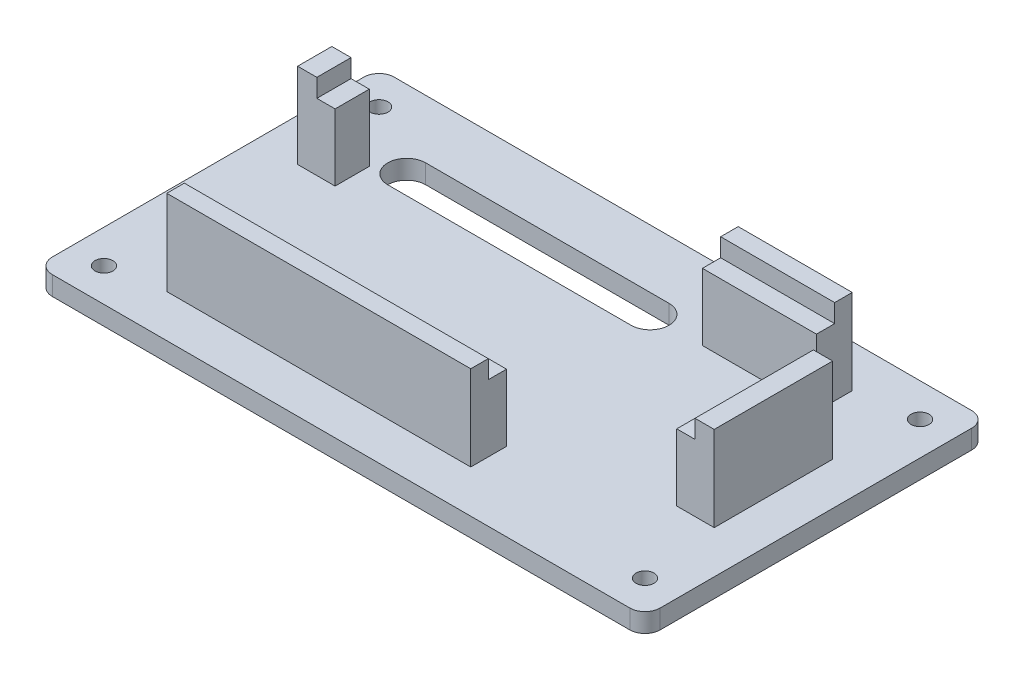
SolidWorks part; units mm, degrees
ref_plane "Front Plane" through (0, 0, 0) normal (0, 0, 1) x (1, 0, 0)
ref_plane "Top Plane" through (0, 0, 0) normal (0, 1, 0) x (1, 0, 0)
ref_plane "Right Plane" through (0, 0, 0) normal (1, 0, 0) x (0, 0, -1)
sketch "Sketch1" plane through (0, 0, 0) normal (0, 1, 0) x (1, 0, 0)
  line L1 (50.8, -28.575) -> (-50.8, -28.575)
  line L2 (50.8, -28.575) -> (50.8, 28.575)
  line L3 (50.8, 28.575) -> (-50.8, 28.575)
  line L4 (-50.8, -28.575) -> (-50.8, 28.575)
  line L5 (50.8, -28.575) -> (-50.8, 28.575) construction
  line L6 (50.8, 28.575) -> (-50.8, -28.575) construction
  point P0 (0, 0)
  dimension "D1" = 57.15
  dimension "D2" = 101.6
extrude "Boss-Extrude1" add sketch "Sketch1" along normal blind 3.175
sketch "Sketch10" plane through (0, 3.175, 0) normal (0, 1, 0) x (1, 0, 0)
  circle A0 centre (-45.212, -22.987) radius 1.5
  circle A1 centre (45.212, 22.987) radius 1.5
  circle A2 centre (-45.212, 22.987) radius 1.5
  circle A3 centre (45.212, -22.987) radius 1.5
  dimension "D1" = 3
extrude "Cut-Extrude3" cut sketch "Sketch10" against normal through all
fillet "Fillet1" radius 2.54 4 edges at (-50.8, 1.5875, 28.575) (-50.8, 1.5875, -28.575) (50.8, 1.5875, 28.575) (50.8, 1.5875, -28.575)
sketch "Sketch11" plane through (0, 3.175, 0) normal (0, 1, 0) x (1, 0, 0)
  line L0 (-33.2243, 15.6253) -> (7.4512, 15.6253) construction
  line L1 (-33.2243, 18.8003) -> (7.4512, 18.8003)
  line L2 (-33.2243, 12.4503) -> (7.4512, 12.4503)
  line L3 (48.26, 28.575) -> (-48.26, 28.575) construction
  arc A0 (-33.2243, 18.8003) -> (-33.2243, 12.4503) centre (-33.2243, 15.6253) ccw
  arc A1 (7.4512, 12.4503) -> (7.4512, 18.8003) centre (7.4512, 15.6253) ccw
  point P2 (-12.8866, 15.6253)
  dimension "D1" = 12.9497
  dimension "D2" = 3.175
extrude "Cut-Extrude4" cut sketch "Sketch11" against normal through all both and the other way through all
ref_plane "Plane3" through (0, 0, 0) normal (1, 0, 0) x (0, 0, -1)
ref_plane "Plane4" through (2.9972, 0, 0) normal (1, 0, 0) x (0, 0, -1)
ref_plane "Plane5" through (-2.9972, 0, 0) normal (1, 0, 0) x (0, 0, -1)
sketch "Sketch12" plane through (2.9972, 0, 0) normal (1, 0, 0) x (0, 0, -1)
  line L0 (-26.035, 0) -> (26.035, 0) construction
  line L1 (0, 0) -> (0, -8.0518) construction
  line L4 (-7.5057, 0) -> (7.5057, 0)
  line L6 (-7.5057, -8.0518) -> (-10.6807, 0)
  line L7 (7.5057, -8.0518) -> (10.6807, 0)
  line L8 (-10.6807, 0) -> (-7.5057, 0)
  line L9 (7.5057, 0) -> (10.6807, 0)
  circle A0 centre (0, -8.0518) radius 2.794
  arc A1 (-7.5057, -8.0518) -> (7.5057, -8.0518) centre (0, -8.0518) ccw
  dimension "D1" = 5.588
  dimension "D2" = 15.0114
  dimension "D3" = 8.0518
  dimension "D4" = 3.175
extrude "Boss-Extrude3" add sketch "Sketch12" along normal mid plane 2.794
sketch "Sketch13" plane through (-2.9972, 0, 0) normal (1, 0, 0) x (0, 0, -1)
  line L0 (0, 0) -> (0, -8.0518) construction
  line L1 (10.6807, 0) -> (-10.6807, 0) construction
  line L2 (-7.5057, 0) -> (7.5057, 0)
  line L5 (-7.5057, -8.0518) -> (-10.6807, 0)
  line L6 (-26.035, 0) -> (26.035, 0) construction
  line L7 (10.6807, 0) -> (-10.6807, 0) construction
  line L8 (-10.6807, 0) -> (-7.5057, 0)
  line L9 (7.5057, -8.0518) -> (10.6807, 0)
  line L10 (7.5057, -8.0518) -> (10.6807, 0) construction
  line L11 (10.6807, 0) -> (7.5057, 0)
  circle A0 centre (0, -8.0518) radius 2.794
  circle A1 centre (0, -8.0518) radius 2.794 construction
  arc A2 (-7.5057, -8.0518) -> (7.5057, -8.0518) centre (0, -8.0518) ccw
extrude "Boss-Extrude4" add sketch "Sketch13" along normal mid plane 2.794
fillet "Fillet4" radius 1 12 edges at (2.9972, -8.0518, -7.5057) (-2.9972, -8.0518, -7.5057) (-2.9972, -8.0518, 7.5057) (2.9972, -8.0518, 7.5057) (-2.9972, 0, 10.6807) (-4.3942, 0, 0) (-1.6002, 0, 0) (-2.9972, 0, -10.6807) (2.9972, 0, -10.6807) (2.9972, 0, 10.6807) (1.6002, 0, 0) (4.3942, 0, 0)
sketch "Sketch14" plane through (0, 3.175, 0) normal (0, 1, 0) x (1, 0, 0)
  line L0 (-50.8, 26.035) -> (-50.8, -26.035) construction
  line L1 (43.688, -21.463) -> (-43.688, -21.463) construction
  line L2 (43.688, -21.463) -> (43.688, 21.463) construction
  line L3 (43.688, 21.463) -> (-43.688, 21.463) construction
  line L4 (-43.688, -21.463) -> (-43.688, 21.463) construction
  line L5 (43.688, -21.463) -> (-43.688, 21.463) construction
  line L6 (43.688, 21.463) -> (-43.688, -21.463) construction
  line L7 (48.26, 28.575) -> (-48.26, 28.575) construction
  line L8 (-39.9669, -18.0213) -> (39.9669, -18.0213) construction
  line L9 (-36.2331, -21.463) -> (14.5669, -21.463)
  line L10 (-36.2331, -21.463) -> (-36.2331, -15.4813)
  line L11 (-36.2331, -15.4813) -> (14.5669, -15.4813)
  line L12 (14.5669, -21.463) -> (14.5669, -15.4813)
  line L13 (39.9669, -18.0213) -> (39.9669, 18.0213) construction
  line L15 (39.9669, 18.0213) -> (-39.9669, 18.0213) construction
  line L16 (16.3412, 21.463) -> (35.3997, 21.463)
  line L17 (16.3412, 21.463) -> (16.3412, 15.4813)
  line L18 (16.3412, 15.4813) -> (35.3997, 15.4813)
  line L19 (35.3997, 21.463) -> (35.3997, 15.4813)
  line L20 (-39.9669, 18.0213) -> (-39.9669, -18.0213) construction
  line L21 (43.688, 9.8933) -> (37.4269, 9.8933)
  line L22 (43.688, 9.8933) -> (43.688, -9.8933)
  line L23 (43.688, -9.8933) -> (37.4269, -9.8933)
  line L24 (37.4269, 9.8933) -> (37.4269, -9.8933)
  line L25 (-43.688, 13.5763) -> (-37.4269, 13.5763)
  line L26 (-43.688, 13.5763) -> (-43.688, 7.8613)
  line L27 (-43.688, 7.8613) -> (-37.4269, 7.8613)
  line L28 (-37.4269, 13.5763) -> (-37.4269, 7.8613)
  point P0 (0, 0)
  dimension "D1" = 7.112
  dimension "D2" = 7.112
  dimension "D3" = 2.54
  dimension "D4" = 25.4
  dimension "D5" = 50.8
  dimension "D6" = 2.54
  dimension "D7" = 8.89
  dimension "D8" = 2.54
  dimension "D9" = 8.128
  dimension "D10" = 8.128
  dimension "D11" = 2.54
  dimension "D12" = 4.445
  dimension "D13" = 5.715
extrude "Boss-Extrude5" add sketch "Sketch14" along normal blind 11.176
sketch "Sketch15" plane through (0, 14.351, 0) normal (0, 1, 0) x (1, 0, 0)
  line L0 (37.4269, -9.8933) -> (43.688, -9.8933) construction
  line L1 (43.688, 9.8933) -> (40.4749, 9.8933)
  line L2 (43.688, 9.8933) -> (43.688, -9.8933)
  line L3 (43.688, -9.8933) -> (40.4749, -9.8933)
  line L4 (40.4749, 9.8933) -> (40.4749, -9.8933)
  line L5 (35.3997, 15.4813) -> (35.3997, 21.463) construction
  line L6 (16.3412, 21.463) -> (35.3997, 21.463)
  line L7 (16.3412, 21.463) -> (16.3412, 18.5293)
  line L8 (16.3412, 18.5293) -> (35.3997, 18.5293)
  line L9 (35.3997, 21.463) -> (35.3997, 18.5293)
  line L10 (-43.688, 7.8613) -> (-37.4269, 7.8613) construction
  line L11 (-43.688, 13.5763) -> (-40.4749, 13.5763)
  line L12 (-43.688, 13.5763) -> (-43.688, 7.8613)
  line L13 (-43.688, 7.8613) -> (-40.4749, 7.8613)
  line L14 (-40.4749, 13.5763) -> (-40.4749, 7.8613)
  line L15 (14.5669, -21.463) -> (14.5669, -15.4813) construction
  line L16 (-36.2331, -21.463) -> (14.5669, -21.463)
  line L17 (-36.2331, -21.463) -> (-36.2331, -18.5293)
  line L18 (-36.2331, -18.5293) -> (14.5669, -18.5293)
  line L19 (14.5669, -21.463) -> (14.5669, -18.5293)
  line L20 (39.9669, -18.0213) -> (39.9669, 18.0213) construction
  line L21 (39.9669, 18.0213) -> (-39.9669, 18.0213) construction
  line L22 (-39.9669, 18.0213) -> (-39.9669, -18.0213) construction
  line L23 (-39.9669, -18.0213) -> (39.9669, -18.0213) construction
  dimension "D1" = 0.508
  dimension "D2" = 0.508
  dimension "D3" = 0.508
  dimension "D4" = 0.508
extrude "Boss-Extrude6" add sketch "Sketch15" along normal blind 3.048
